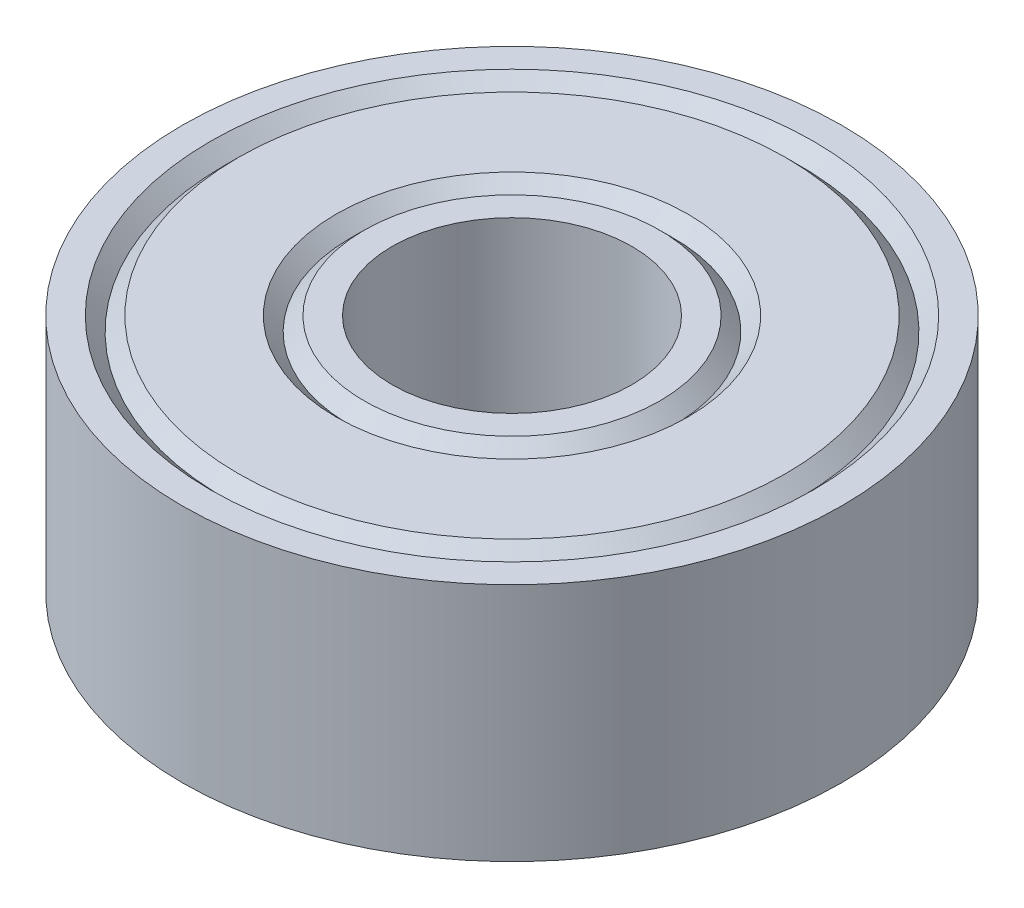
SolidWorks part; units mm, degrees
ref_plane "Front Plane" through (0, 0, 0) normal (0, 0, 1) x (1, 0, 0)
ref_plane "Top Plane" through (0, 0, 0) normal (0, 1, 0) x (1, 0, 0)
ref_plane "Right Plane" through (0, 0, 0) normal (1, 0, 0) x (0, 0, -1)
sketch "Sketch1" plane through (0, 0, 0) normal (0, 0, 1) x (1, 0, 0)
  line L0 (0, 2) -> (0, -2) construction
  line L1 (-2, 2) -> (-2.4667, 2)
  line L2 (-2, 2) -> (-2, -2)
  line L3 (-2, -2) -> (-2.4667, -2)
  line L4 (-5.5, 2) -> (-5.5, -2)
  line L5 (-5.0333, 2) -> (-4.8, 1.7667)
  line L6 (-4.8, 1.7667) -> (-4.5667, 2)
  line L7 (-2.9333, 2) -> (-2.7, 1.7667)
  line L8 (-2.7, 1.7667) -> (-2.4667, 2)
  line L9 (-5.0333, -2) -> (-4.8, -1.7667)
  line L10 (-4.8, -1.7667) -> (-4.5667, -2)
  line L11 (-2.9333, -2) -> (-2.7, -1.7667)
  line L12 (-2.7, -1.7667) -> (-2.4667, -2)
  line L13 (-2.9333, -2) -> (-4.5667, -2)
  line L14 (-5.0333, -2) -> (-5.5, -2)
  line L15 (-5.0333, 2) -> (-5.5, 2)
  line L16 (-2.9333, 2) -> (-4.5667, 2)
  line L17 (-4.8, 1.7667) -> (-2.7, 1.7667) construction
  line L18 (-4.8, 1.7667) -> (-4.8, -1.7667) construction
  line L19 (-2.7, -1.7667) -> (-4.8, -1.7667) construction
  line L20 (-2.7, 1.7667) -> (-2.7, -1.7667) construction
  line L21 (-4.8, 0) -> (-4.1, 0) construction
  line L22 (-2.4667, 2) -> (-2.9333, 2) construction
  line L23 (-4.1, 0) -> (-3.4, 0) construction
  line L24 (-4.8, 0) -> (-5.5, 0) construction
  line L25 (-3.4, 0) -> (-2.7, 0) construction
  line L26 (-2.7, 0) -> (-2, 0) construction
  dimension "D1" = 4
  dimension "D2" = 4
  dimension "D3" = 11
revolve "Revolve1" add sketch "Sketch1" angle 360 about L0
